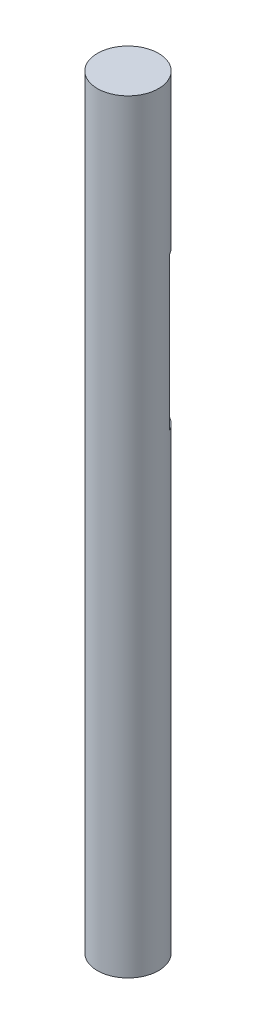
SolidWorks part; units mm, degrees
ref_plane "Front" through (0, 0, 0) normal (0, 0, 1) x (1, 0, 0)
ref_plane "Top" through (0, 0, 0) normal (0, 1, 0) x (1, 0, 0)
ref_plane "Right" through (0, 0, 0) normal (1, 0, 0) x (0, 0, -1)
sketch "Esquisse1" plane through (0, 0, 0) normal (0, 1, 0) x (1, 0, 0)
  circle A0 centre (0, 0) radius 4
  dimension "D1" = 8
extrude "Boss.-Extru.1" add sketch "Esquisse1" along normal blind 100
ref_plane "Plan1" through (0, 80, 0) normal (0, 1, 0) x (1, 0, 0)
sketch "Esquisse2" plane through (0, 80, 0) normal (0, 1, 0) x (1, 0, 0)
  line L1 (-3.4641, 2) -> (3.4641, 2)
  line L2 (-3.4641, 2) -> (-3.4641, 10)
  line L3 (-3.4641, 10) -> (3.4641, 10)
  line L4 (3.4641, 2) -> (3.4641, 10)
  circle A0 centre (0, 0) radius 4 construction
  point P6 (0, 0)
  dimension "D1" = 2
  dimension "D2" = 10
extrude "Enlèv. mat.-Extru.1" cut sketch "Esquisse2" against normal blind 20
